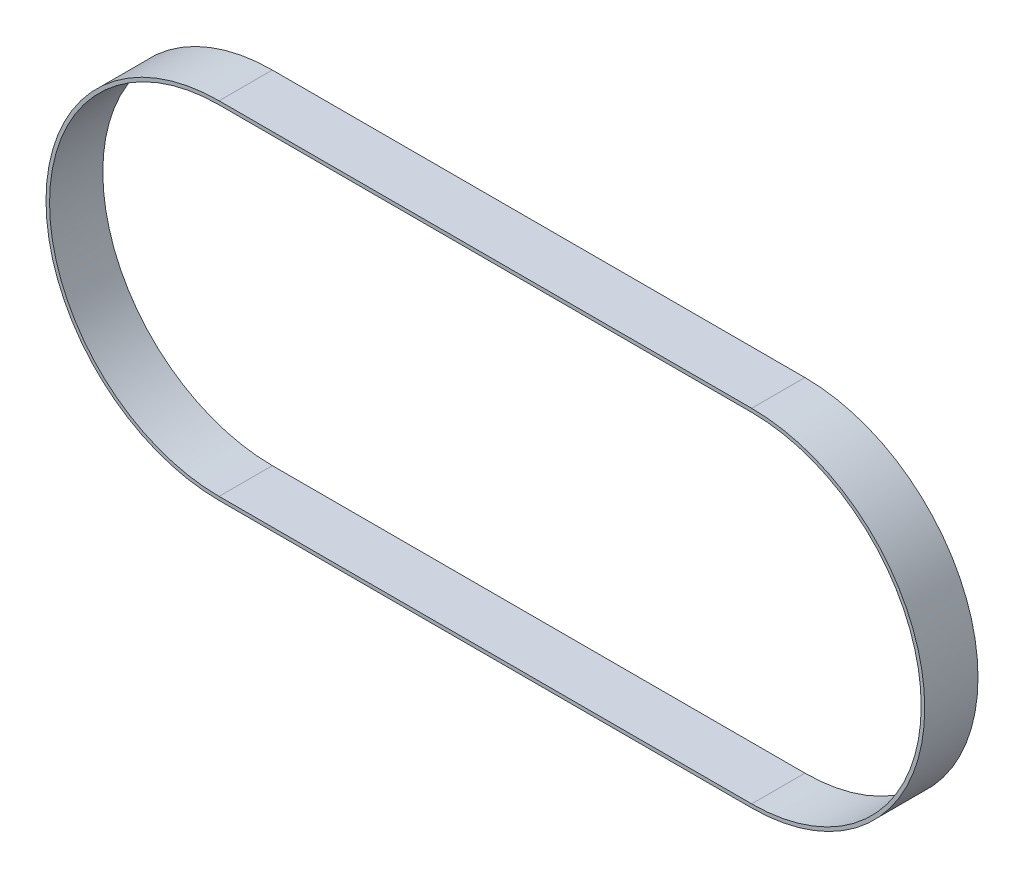
SolidWorks part; units mm, degrees
material "Rubber"
ref_plane "Front Plane" through (0, 0, 0) normal (0, 0, 1) x (1, 0, 0)
ref_plane "Top Plane" through (0, 0, 0) normal (0, 1, 0) x (1, 0, 0)
ref_plane "Right Plane" through (0, 0, 0) normal (1, 0, 0) x (0, 0, -1)
sketch "Sketch1" plane through (0, 0, 0) normal (0, 0, 1) x (1, 0, 0)
  line L0 (-75, 0) -> (75, 0) construction
  line L1 (-75, 47.7465) -> (75, 47.7465)
  line L2 (-75, -47.7465) -> (75, -47.7465)
  line L3 (-75, 48.7465) -> (75, 48.7465)
  line L4 (-75, -48.7465) -> (75, -48.7465)
  arc A0 (-75, 47.7465) -> (-75, -47.7465) centre (-75, 0) ccw
  arc A1 (75, -47.7465) -> (75, 47.7465) centre (75, 0) ccw
  arc A2 (75, -48.7465) -> (75, 48.7465) centre (75, 0) ccw
  arc A3 (-75, 48.7465) -> (-75, -48.7465) centre (-75, 0) ccw
  point P2 (0, 0)
  dimension "D1" = 150
  dimension "D2" = 47.7465
  dimension "D3" = 1
extrude "Boss-Extrude1" add sketch "Sketch1" along normal blind 15 contours A0 L2 A1 L1
